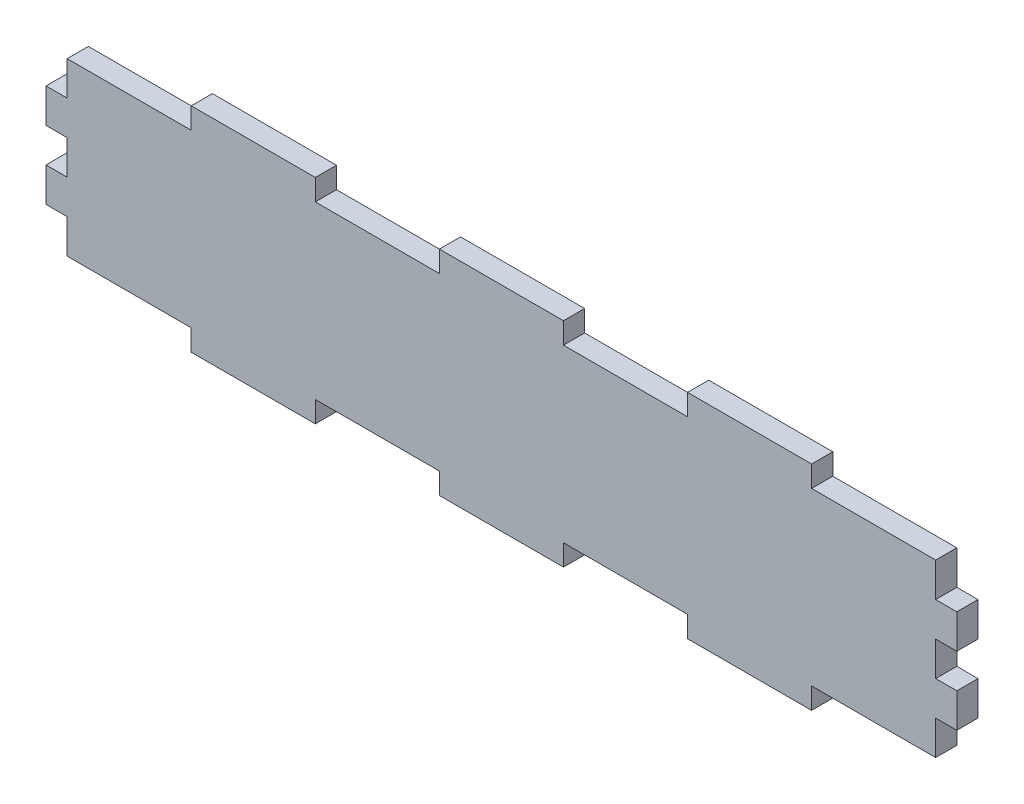
SolidWorks part; units mm, degrees
ref_plane "Front Plane" through (0, 0, 0) normal (0, 0, 1) x (1, 0, 0)
ref_plane "Top Plane" through (0, 0, 0) normal (0, 1, 0) x (1, 0, 0)
ref_plane "Right Plane" through (0, 0, 0) normal (1, 0, 0) x (0, 0, -1)
sketch "Sketch2" plane through (0, 0, 0) normal (0, 0, 1) x (1, 0, 0)
  line L0 (0, 40.4) -> (0, 0) construction
  line L4 (205.1, 40.4) -> (205.1, 24.24)
  line L7 (205.1, 24.24) -> (215.1, 24.24)
  line L8 (205.1, 8.08) -> (215.1, 8.08)
  line L11 (-205.1, 0) -> (205.1, 0) construction
  line L13 (205.1, 8.08) -> (205.1, -8.08)
  line L15 (215.1, 8.08) -> (215.1, 24.24)
  line L16 (205.1, 40.4) -> (146.5, 40.4)
  line L38 (29.3, 40.4) -> (87.9, 40.4)
  line L39 (0, -40.4) -> (0, 0) construction
  line L40 (146.5, 40.4) -> (146.5, 50.4)
  line L41 (87.9, 40.4) -> (87.9, 50.4)
  line L42 (29.3, 40.4) -> (29.3, 50.4)
  line L56 (205.1, 40.4) -> (205.1, 24.24)
  line L57 (146.5, 50.4) -> (87.9, 50.4)
  line L59 (87.9, 40.4) -> (29.3, 40.4)
  line L60 (146.5, 40.4) -> (205.1, 40.4)
  line L61 (29.3, 50.4) -> (-29.3, 50.4)
  line L62 (29.3, -50.4) -> (-29.3, -50.4)
  line L63 (146.5, -40.4) -> (205.1, -40.4)
  line L64 (87.9, -40.4) -> (29.3, -40.4)
  line L66 (146.5, -50.4) -> (87.9, -50.4)
  line L67 (29.3, -40.4) -> (29.3, -50.4)
  line L68 (87.9, -40.4) -> (87.9, -50.4)
  line L69 (146.5, -40.4) -> (146.5, -50.4)
  line L70 (29.3, -40.4) -> (87.9, -40.4)
  line L71 (205.1, -40.4) -> (146.5, -40.4)
  line L72 (215.1, -8.08) -> (215.1, -24.24)
  line L73 (205.1, -8.08) -> (215.1, -8.08)
  line L74 (205.1, -24.24) -> (215.1, -24.24)
  line L75 (205.1, -40.4) -> (205.1, -24.24)
  line L76 (-205.1, -40.4) -> (-205.1, -24.24)
  line L77 (-205.1, -24.24) -> (-215.1, -24.24)
  line L78 (-205.1, -8.08) -> (-215.1, -8.08)
  line L79 (-215.1, -8.08) -> (-215.1, -24.24)
  line L80 (-205.1, -40.4) -> (-146.5, -40.4)
  line L81 (-29.3, -40.4) -> (-87.9, -40.4)
  line L82 (-146.5, -40.4) -> (-146.5, -50.4)
  line L83 (-87.9, -40.4) -> (-87.9, -50.4)
  line L84 (-29.3, -40.4) -> (-29.3, -50.4)
  line L85 (-146.5, -50.4) -> (-87.9, -50.4)
  line L86 (-87.9, -40.4) -> (-29.3, -40.4)
  line L87 (-146.5, -40.4) -> (-205.1, -40.4)
  line L88 (-146.5, 40.4) -> (-205.1, 40.4)
  line L89 (-87.9, 40.4) -> (-29.3, 40.4)
  line L90 (-146.5, 50.4) -> (-87.9, 50.4)
  line L91 (-205.1, 40.4) -> (-205.1, 24.24)
  line L92 (-29.3, 40.4) -> (-29.3, 50.4)
  line L96 (-87.9, 40.4) -> (-87.9, 50.4)
  line L97 (-146.5, 40.4) -> (-146.5, 50.4)
  line L98 (-29.3, 40.4) -> (-87.9, 40.4)
  line L99 (-205.1, 40.4) -> (-146.5, 40.4)
  line L100 (-215.1, 8.08) -> (-215.1, 24.24)
  line L101 (-205.1, 8.08) -> (-205.1, -8.08)
  line L102 (-205.1, 8.08) -> (-215.1, 8.08)
  line L103 (-205.1, 24.24) -> (-215.1, 24.24)
  line L104 (-205.1, 40.4) -> (-205.1, 24.24)
  line L105 (205.1, 8.08) -> (205.1, -8.08)
  line L106 (205.1, -24.24) -> (205.1, -40.4)
  line L107 (-205.1, -24.24) -> (-205.1, -40.4)
  line L108 (-205.1, 8.08) -> (-205.1, -8.08)
  point P0 (0, 0)
  point P18 (0, 20.2)
  point P33 (0, -20.2)
  dimension "D1" = 58.6
  dimension "D2" = 205.1
extrude "Boss-Extrude1" add sketch "Sketch2" along normal blind 10 contours L91 L103 L100 L102 L101 L78 L79 L77 L76 L80 L82 L85 L83 L81 L84 L62 L67 L64 L68 L66 L69 L63 L75 L74 L72 L73 L13 L8 L15 L7 L4 L16 L40 L57 L41 L38 L42 L61 L92 L89 L96 L90 L97 L88
